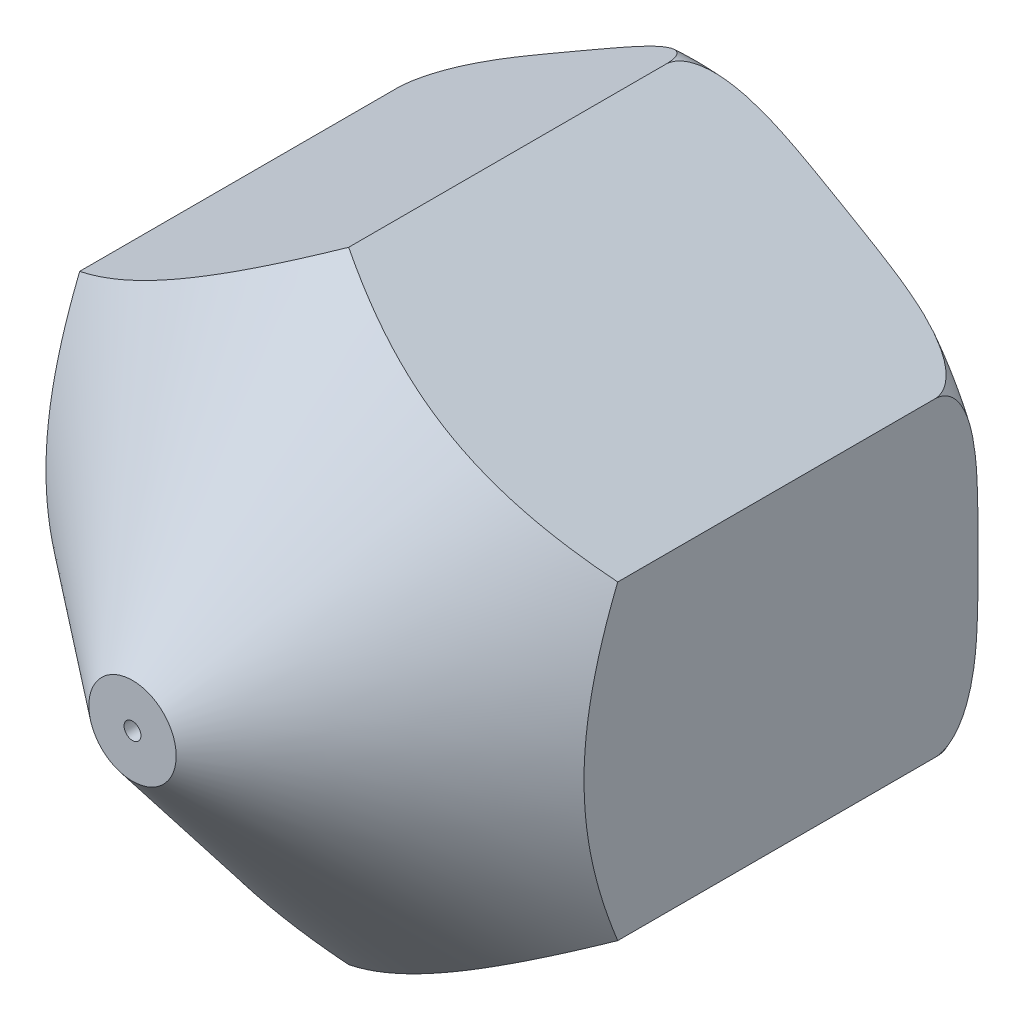
SolidWorks part; units mm, degrees
material "Латунь"
ref_plane "Спереди" through (0, 0, 0) normal (0, 0, 1) x (1, 0, 0)
ref_plane "Сверху" through (0, 0, 0) normal (0, 1, 0) x (1, 0, 0)
ref_plane "Справа" through (0, 0, 0) normal (1, 0, 0) x (0, 0, -1)
sketch "Эскиз1" plane through (0, 0, 0) normal (0, 0, 1) x (1, 0, 0)
  line L1 (6.4663, 0) -> (3.2332, 5.6) construction
  line L2 (3.2332, 5.6) -> (-3.2332, 5.6) construction
  line L3 (-3.2332, 5.6) -> (-6.4663, 0) construction
  line L4 (-6.4663, 0) -> (-3.2332, -5.6) construction
  line L5 (-3.2332, -5.6) -> (3.2332, -5.6) construction
  line L6 (3.2332, -5.6) -> (6.4663, 0) construction
  circle A0 centre (0, 0) radius 5.6 construction
  circle A1 centre (0, 0) radius 6.4663
  dimension "D1" = 11.2
extrude "Бобышка-Вытянуть1" add sketch "Эскиз1" along normal blind 7.5
sketch "Эскиз2" plane through (0, 0, 7.5) normal (0, 0, 1) x (1, 0, 0)
  circle A0 centre (0, 0) radius 6.4663
extrude "Бобышка-Вытянуть2" add sketch "Эскиз2" along normal blind 4.5 draft 51
sketch "Эскиз3" plane through (0, 0, 0) normal (0, 0, -1) x (-1, 0, 0)
  line L1 (0, 6.4663) -> (-5.6, 3.2332)
  line L2 (-5.6, 3.2332) -> (-5.6, -3.2332)
  line L3 (-5.6, -3.2332) -> (0, -6.4663)
  line L4 (0, -6.4663) -> (5.6, -3.2332)
  line L5 (5.6, -3.2332) -> (5.6, 3.2332)
  line L6 (5.6, 3.2332) -> (0, 6.4663)
  circle A0 centre (0, 0) radius 5.6 construction
fillet "Скругление1" radius 0.9 1 edges at (6.4663, 0, 0)
extrude "Вырез-Вытянуть2" cut sketch "Эскиз3" against normal through all flip side to cut contours L1 L2 L3 L4 L5 L6
sketch "Эскиз4" plane through (0, 0, 0) normal (0, 0, -1) x (-1, 0, 0)
  circle A0 centre (0, 0) radius 3.25
  dimension "D1" = 6.5
extrude "Вырез-Вытянуть3" cut sketch "Эскиз4" against normal blind 8
sketch "Эскиз6" plane through (0, 0, 12) normal (0, 0, 1) x (1, 0, 0)
  circle A0 centre (0, 0) radius 0.175
  dimension "D1" = 0.35
extrude "Вырез-Вытянуть4" cut sketch "Эскиз6" against normal through all
sketch "Эскиз5" plane through (0, 0, 8) normal (0, 0, -1) x (-1, 0, 0)
  circle A0 centre (0, 0) radius 1.09
  dimension "D1" = 2.18
extrude "Вырез-Вытянуть5" cut sketch "Эскиз5" against normal blind 3.5 draft 15
